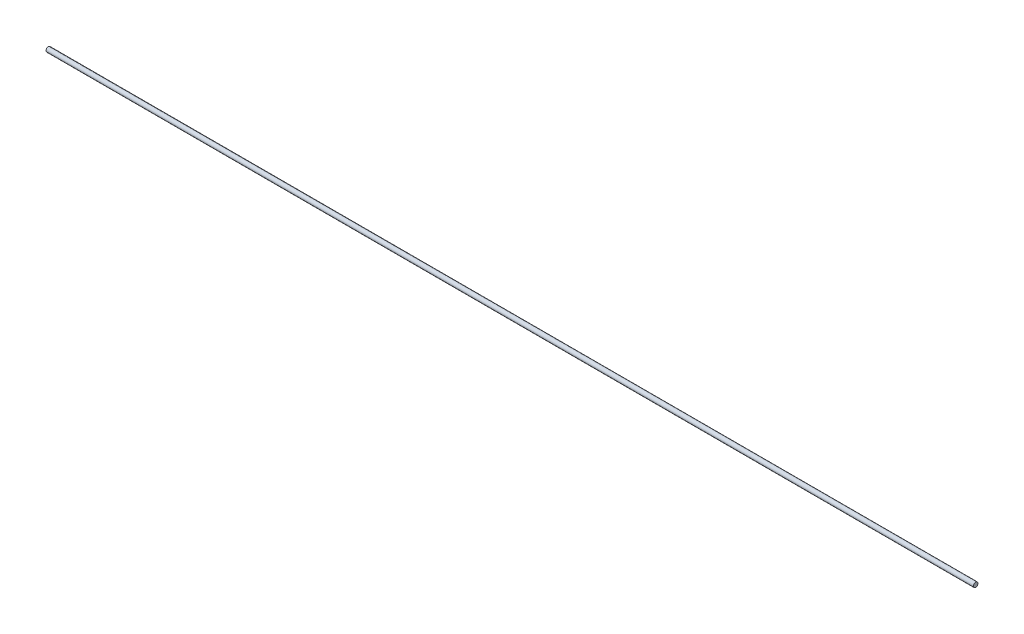
SolidWorks part; units mm, degrees
ref_plane "前视基准面" through (0, 0, 0) normal (0, 0, 1) x (1, 0, 0)
ref_plane "上视基准面" through (0, 0, 0) normal (0, 1, 0) x (1, 0, 0)
ref_plane "右视基准面" through (0, 0, 0) normal (1, 0, 0) x (0, 0, -1)
sketch "草图1" plane through (0, 0, 0) normal (1, 0, 0) x (0, 0, -1)
  circle A0 centre (0, 0) radius 0.5
  dimension "D1" = 1
extrude "凸台-拉伸1" add sketch "草图1" along normal blind 200
